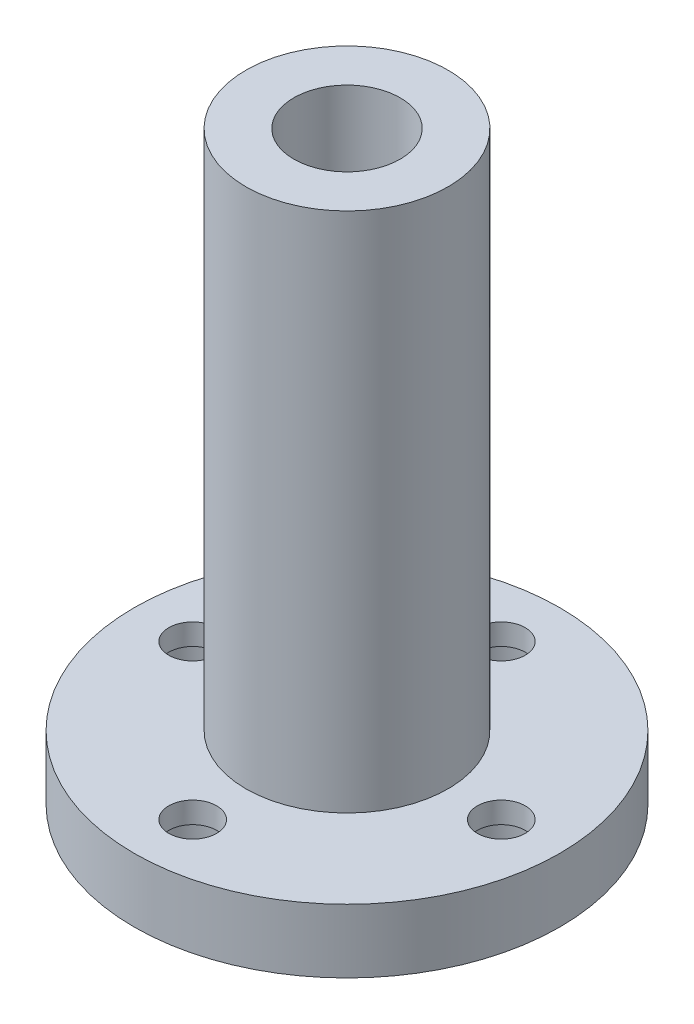
SolidWorks part; units mm, degrees
ref_plane "Спереди" through (0, 0, 0) normal (0, 0, 1) x (1, 0, 0)
ref_plane "Сверху" through (0, 0, 0) normal (0, 1, 0) x (1, 0, 0)
ref_plane "Справа" through (0, 0, 0) normal (1, 0, 0) x (0, 0, -1)
sketch "Эскиз1" plane through (0, 0, 0) normal (0, 0, 1) x (1, 0, 0)
  line L0 (0, 53.581) -> (0, -51.994) construction
  line L1 (0, 0) -> (121.0498, 0) construction
  line L2 (5, 55) -> (5, 0)
  line L3 (5, 0) -> (20, 0)
  line L4 (20, 0) -> (20, 6)
  line L5 (20, 6) -> (9.5, 6)
  line L6 (9.5, 6) -> (9.5, 55)
  line L7 (9.5, 55) -> (5, 55)
  dimension "D1" = 55
  dimension "D2" = 20
  dimension "D3" = 9.5
  dimension "D4" = 5
  dimension "D5" = 6
revolve "Повернуть1" add sketch "Эскиз1" angle 360 about L0
sketch "Эскиз2" plane through (0, 6, 0) normal (0, 1, 0) x (1, 0, 0)
  line L0 (-29.5505, 0) -> (29.5505, 0) construction
  line L1 (0, 24.5855) -> (0, -24.5855) construction
  circle A0 centre (14.5, 0) radius 2.25
  circle A1 centre (0, -14.5) radius 2.25
  circle A2 centre (-14.5, 0) radius 2.25
  circle A3 centre (0, 14.5) radius 2.25
  circle A4 centre (0, 0) radius 14.5 construction
  dimension "D1" = 29
  dimension "D2" = 4.5
extrude "Вырез-Вытянуть1" cut sketch "Эскиз2" against normal through all
sketch "Эскиз3" plane through (0, 0, 0) normal (0, -1, 0) x (1, 0, 0)
  circle A0 centre (-14.5, 0) radius 3.75
  circle A1 centre (0, 14.5) radius 3.75
  circle A2 centre (14.5, 0) radius 3.75
  circle A3 centre (0, -14.5) radius 3.75
  dimension "D1" = 7.5
extrude "Вырез-Вытянуть2" cut sketch "Эскиз3" against normal blind 4
